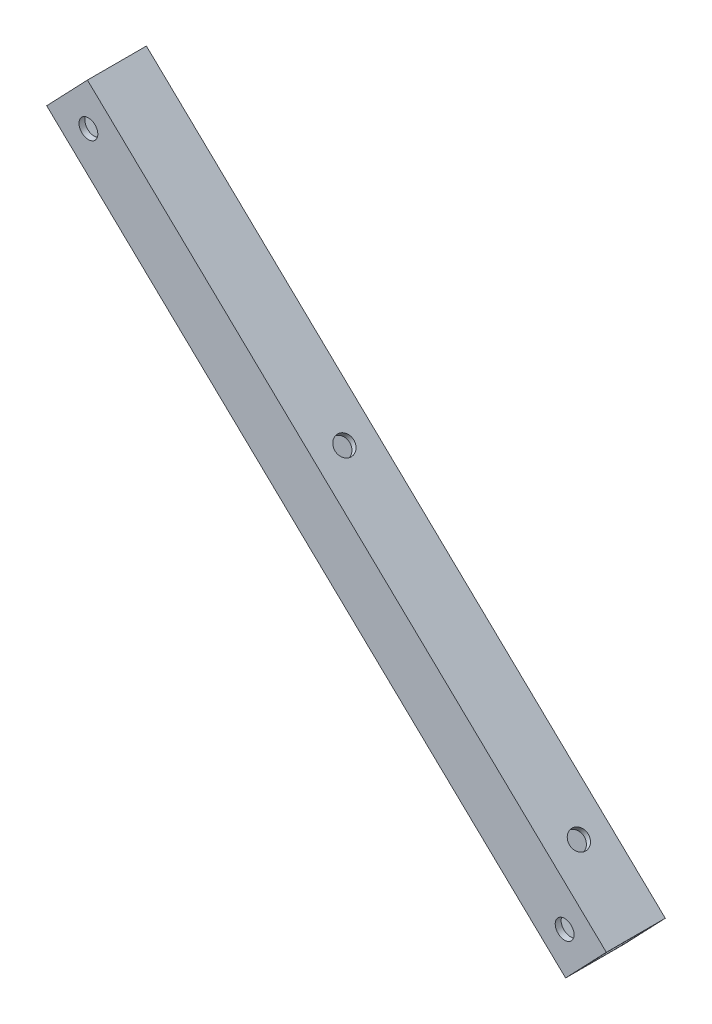
SolidWorks part; units mm, degrees
ref_plane "正面" through (0, 0, 0) normal (0, 0, 1) x (1, 0, 0)
ref_plane "平面" through (0, 0, 0) normal (0, 1, 0) x (1, 0, 0)
ref_plane "右側面" through (0, 0, 0) normal (1, 0, 0) x (0, 0, -1)
sketch "ｽｹｯﾁ2" plane through (0, 0, 0) normal (0, 0, 1) x (1, 0, 0)
  line L0 (-3.7761, 84.2848) -> (76.9904, 7.0917)
  line L1 (83.0716, 8.196) -> (-3.936, 91.3541)
  line L2 (-3.936, 91.3541) -> (-10.8454, 84.1249)
  line L3 (-10.8454, 84.1249) -> (77.1503, 0.0225)
  line L4 (77.1503, 0.0225) -> (84.0597, 7.2517)
  line L5 (84.0597, 7.2517) -> (83.0716, 8.196)
  circle A0 centre (-3.7761, 84.2848) radius 1.6
  circle A1 centre (76.9904, 7.0917) radius 1.6
  dimension "D1" = 111.7229
  dimension "D4" = 5
  dimension "D5" = 5
  dimension "D2" = 5
  dimension "D3" = 5
extrude "ﾎﾞｽ - 押し出し1" add sketch "ｽｹｯﾁ2" along normal blind 10
sketch "ｽｹｯﾁ3" plane through (40.3084, -38.525, 0) normal (0.7229, -0.6909, 0) x (0, 0, -1)
  line L0 (-10, 53.322) -> (0, 53.322) construction
  line L1 (-9, 54.322) -> (-1, 54.322)
  line L2 (-9, 54.322) -> (-9, 62.322)
  line L3 (-9, 62.322) -> (-1, 62.322)
  line L4 (-1, 54.322) -> (-1, 62.322)
  line L5 (-10, 53.322) -> (-10, 63.322) construction
  dimension "D1" = 1
  dimension "D2" = 1
  dimension "D3" = 8
  dimension "D4" = 8
extrude "ｶｯﾄ - 押し出し1" cut sketch "ｽｹｯﾁ3" against normal through all
sketch "ｽｹｯﾁ5" plane through (36.842, 38.5475, 0) normal (-0.6909, -0.7229, 0) x (0.7229, -0.6909, 0)
  line L0 (-65.965, 0) -> (55.7579, 0) construction
  line L1 (-65.965, 5) -> (55.7579, 5)
  line L2 (-65.965, 10) -> (-65.965, 0) construction
  line L3 (55.7579, 10) -> (55.7579, 0) construction
  circle A0 centre (42.3964, 5) radius 1.6
  circle A1 centre (-12.6036, 5) radius 1.6
  point P13 (-5.1036, 5)
  dimension "D1" = 5
  dimension "D3" = 7.5
  dimension "D2" = 55
extrude "ｶｯﾄ - 押し出し3" cut sketch "ｽｹｯﾁ5" against normal blind 10 contours L1 A1 | L1 A1 | L1 A0 | L1 A0
